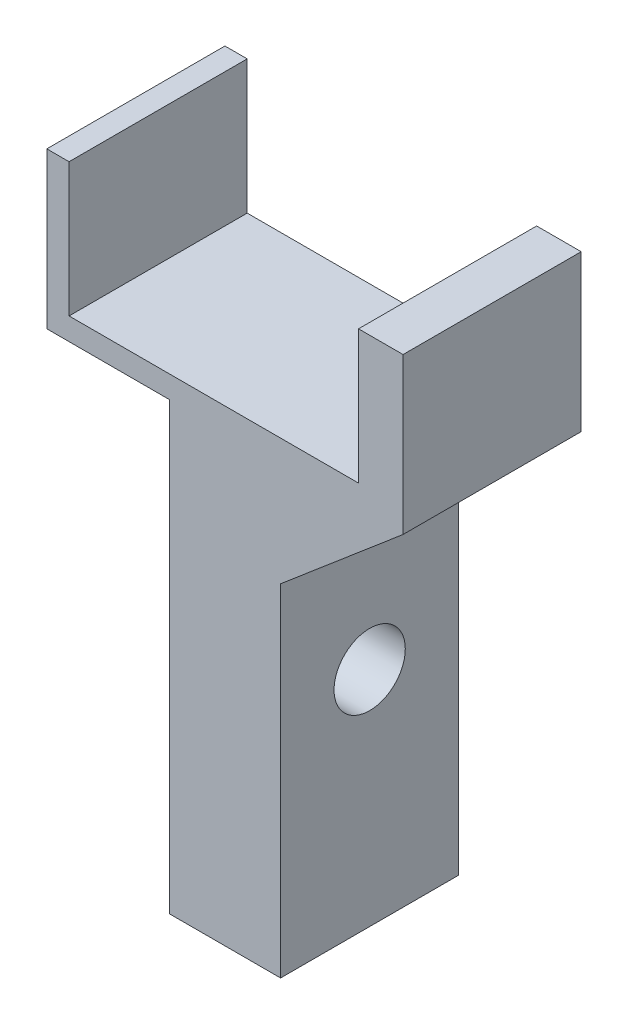
SolidWorks part; units mm, degrees
ref_plane "前视基准面" through (0, 0, 0) normal (0, 0, 1) x (1, 0, 0)
ref_plane "上视基准面" through (0, 0, 0) normal (0, 1, 0) x (1, 0, 0)
ref_plane "右视基准面" through (0, 0, 0) normal (1, 0, 0) x (0, 0, -1)
sketch "草图6" plane through (0, 0, 0) normal (0, 0, 1) x (1, 0, 0)
  line L0 (-5, 20) -> (-10.5, 20)
  line L1 (0, 0) -> (-5, 0)
  line L2 (0, 0) -> (0, 15.3336)
  line L3 (5.5, 20) -> (0, 15.3336)
  line L4 (-5, 0) -> (-5, 20)
  line L5 (5.5, 27) -> (-10.5, 27)
  line L6 (5.5, 27) -> (5.5, 20)
  line L8 (-10.5, 27) -> (-10.5, 20)
  dimension "D1" = 5
  dimension "D3" = 5.5
  dimension "D4" = 16
  dimension "D5" = 7
extrude "凸台-拉伸4" add sketch "草图6" along normal blind 8
sketch "草图7" plane through (0, 0, 0) normal (0, 0, -1) x (-1, 0, 0)
  line L0 (-5.5, 20) -> (-5.5, 27) construction
  line L1 (-3.5, 27.4991) -> (9.5, 27.4991)
  line L2 (-3.5, 27.4991) -> (-3.5, 21)
  line L3 (-3.5, 21) -> (9.5, 21)
  line L4 (9.5, 27.4991) -> (9.5, 21)
  line L5 (10.5, 27) -> (10.5, 20) construction
  line L6 (10.5, 20) -> (5, 20) construction
  dimension "D1" = 2
  dimension "D2" = 1
  dimension "D3" = 1
extrude "切除-拉伸3" cut sketch "草图7" against normal through all
sketch "草图8" plane through (0, 0, 0) normal (1, 0, 0) x (0, 0, -1)
  line L0 (-4, 0) -> (-4, 10.9663) construction
  line L1 (-8, 0) -> (0, 0) construction
  circle A0 centre (-4, 10) radius 1.6
  dimension "D1" = 3.2
  dimension "D2" = 10
extrude "切除-拉伸4" cut sketch "草图8" against normal through all
